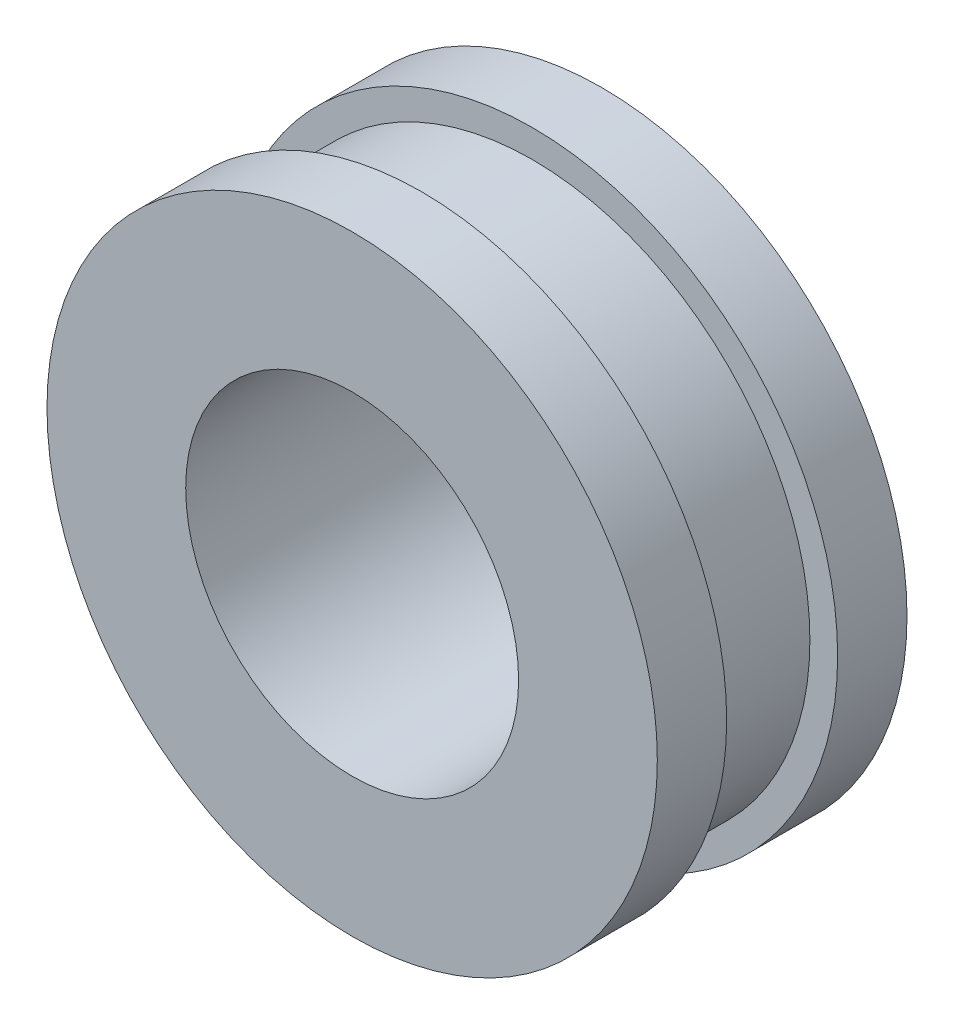
SolidWorks part; units mm, degrees
ref_plane "前视基准面" through (0, 0, 0) normal (0, 0, 1) x (1, 0, 0)
ref_plane "上视基准面" through (0, 0, 0) normal (0, 1, 0) x (1, 0, 0)
ref_plane "右视基准面" through (0, 0, 0) normal (1, 0, 0) x (0, 0, -1)
other "Configuration Table"
sketch "草图2" plane through (0, 0, 0) normal (0, 0, 1) x (1, 0, 0)
  circle A0 centre (0, 0) radius 5.5
  circle A1 centre (0, 0) radius 3
  dimension "D1" = 11
  dimension "D2" = 6
extrude "凸台-拉伸1" add sketch "草图2" along normal mid plane 4.5
sketch "草图3" plane through (0, 0, 0) normal (0, 0, 1) x (1, 0, 0)
  circle A0 centre (0, 0) radius 5
  dimension "D1" = 10
extrude "切除-拉伸1" cut sketch "草图3" against normal mid plane 2 flip side to cut
